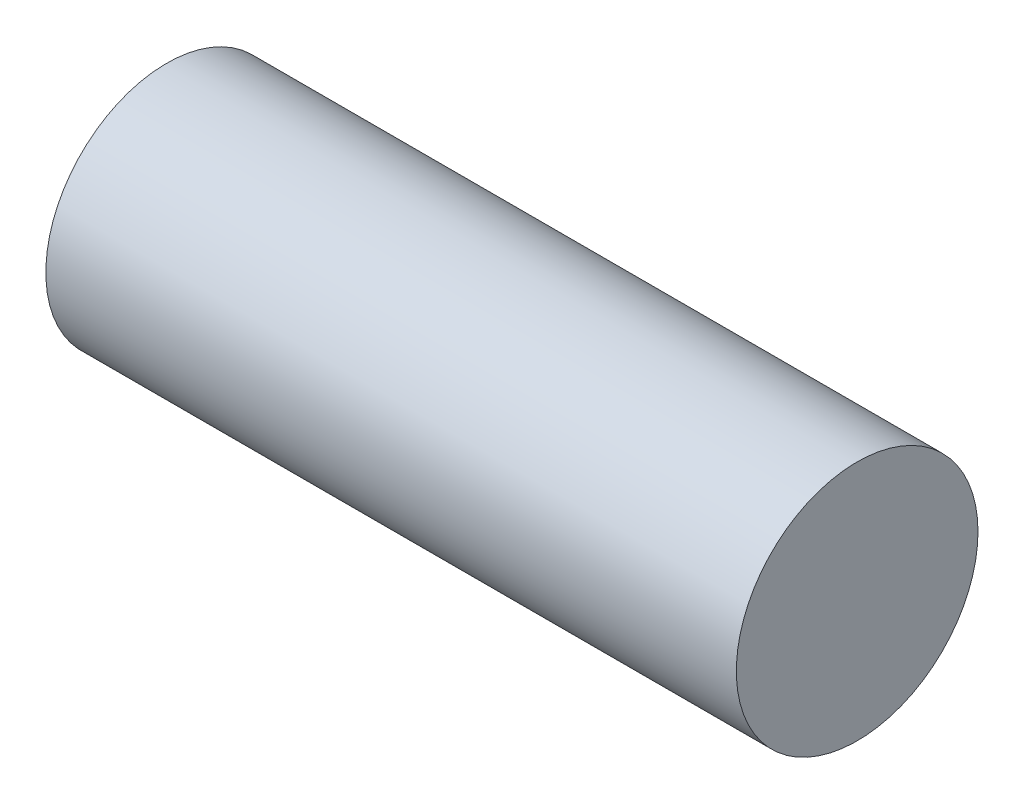
SolidWorks part; units mm, degrees
ref_plane "Front Plane" through (0, 0, 0) normal (0, 0, 1) x (1, 0, 0)
ref_plane "Top Plane" through (0, 0, 0) normal (0, 1, 0) x (1, 0, 0)
ref_plane "Right Plane" through (0, 0, 0) normal (1, 0, 0) x (0, 0, -1)
sketch "Sketch1" plane through (0, 0, 0) normal (1, 0, 0) x (0, 0, -1)
  circle A0 centre (-1640, -80) radius 140
extrude "Boss-Extrude1" add sketch "Sketch1" along normal blind 800 from offset 200
